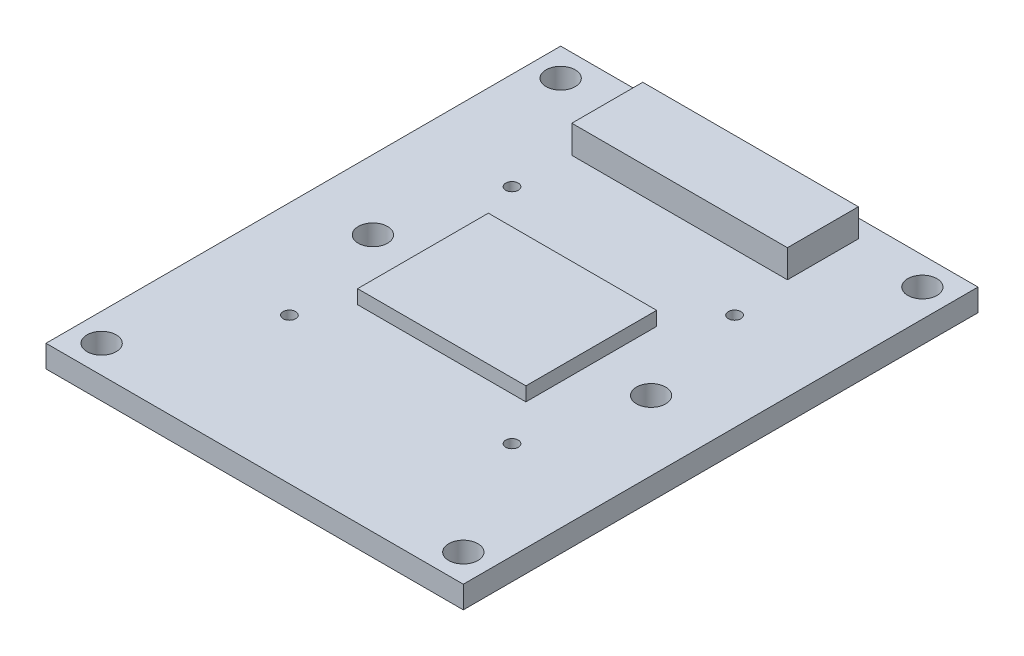
SolidWorks part; units mm, degrees
ref_plane "前视基准面" through (0, 0, 0) normal (0, 0, 1) x (1, 0, 0)
ref_plane "上视基准面" through (0, 0, 0) normal (0, 1, 0) x (1, 0, 0)
ref_plane "右视基准面" through (0, 0, 0) normal (1, 0, 0) x (0, 0, -1)
sketch "草图1" plane through (0, 0, 0) normal (0, 1, 0) x (1, 0, 0)
  line L0 (0, -18.5) -> (30, -18.5) construction
  line L1 (0, 0) -> (30, 0)
  line L2 (0, 0) -> (0, -37)
  line L3 (0, -37) -> (30, -37)
  line L4 (30, 0) -> (30, -37)
  line L5 (2, -2) -> (28, -2) construction
  line L6 (2, -2) -> (2, -35) construction
  line L7 (2, -35) -> (28, -35) construction
  line L8 (28, -2) -> (28, -35) construction
  line L9 (7, -10.5) -> (23, -10.5) construction
  line L10 (7, -10.5) -> (7, -26.5) construction
  line L11 (7, -26.5) -> (23, -26.5) construction
  line L12 (23, -10.5) -> (23, -26.5) construction
  circle A0 centre (2, -2) radius 1.05
  circle A1 centre (28, -2) radius 1.05
  circle A2 centre (2, -35) radius 1.05
  circle A3 centre (28, -35) radius 1.05
  circle A4 centre (7, -10.5) radius 0.45
  circle A5 centre (23, -10.5) radius 0.45
  circle A6 centre (7, -26.5) radius 0.45
  circle A7 centre (23, -26.5) radius 0.45
  circle A8 centre (5, -18.5) radius 1.05
  circle A9 centre (25, -18.5) radius 1.05
  dimension "D7" = 2.1
  dimension "D8" = 2.1
  dimension "D9" = 2.1
  dimension "D10" = 2.1
  dimension "D15" = 0.9
  dimension "D16" = 0.9
  dimension "D17" = 0.9
  dimension "D18" = 0.9
  dimension "D22" = 2.1
  dimension "D23" = 2.1
  dimension "D1" = 37
  dimension "D2" = 30
  dimension "D3" = 2
  dimension "D4" = 2
  dimension "D5" = 2
  dimension "D6" = 2
  dimension "D11" = 10.5
  dimension "D12" = 7
  dimension "D13" = 16
  dimension "D14" = 16
  dimension "D19" = 18.5
  dimension "D20" = 5
  dimension "D21" = 20
extrude "凸台-拉伸1" add sketch "草图1" along normal blind 1.6
sketch "草图2" plane through (0, 1.6, 0) normal (0, 1, 0) x (1, 0, 0)
  line L0 (0, 0) -> (0, -37) construction
  line L1 (8.8, -14) -> (20.9, -14)
  line L2 (8.8, -14) -> (8.8, -23.4)
  line L3 (8.8, -23.4) -> (20.9, -23.4)
  line L4 (20.9, -14) -> (20.9, -23.4)
  line L5 (0, -37) -> (30, -37) construction
  dimension "D1" = 8.8
  dimension "D2" = 13.6
  dimension "D3" = 12.1
  dimension "D4" = 9.4
extrude "凸台-拉伸2" add sketch "草图2" along normal blind 1
sketch "草图3" plane through (0, 1.6, 0) normal (0, 1, 0) x (1, 0, 0)
  line L5 (0, 0) -> (0, -37) construction
  line L6 (7.2, -1.3) -> (22.7, -1.3)
  line L7 (7.2, -1.3) -> (7.2, -6.4)
  line L8 (7.2, -6.4) -> (22.7, -6.4)
  line L9 (22.7, -1.3) -> (22.7, -6.4)
  line L10 (30, 0) -> (0, 0) construction
  dimension "D1" = 7.2
  dimension "D2" = 6.4
  dimension "D3" = 15.5
  dimension "D4" = 5.1
extrude "凸台-拉伸3" add sketch "草图3" along normal blind 2
